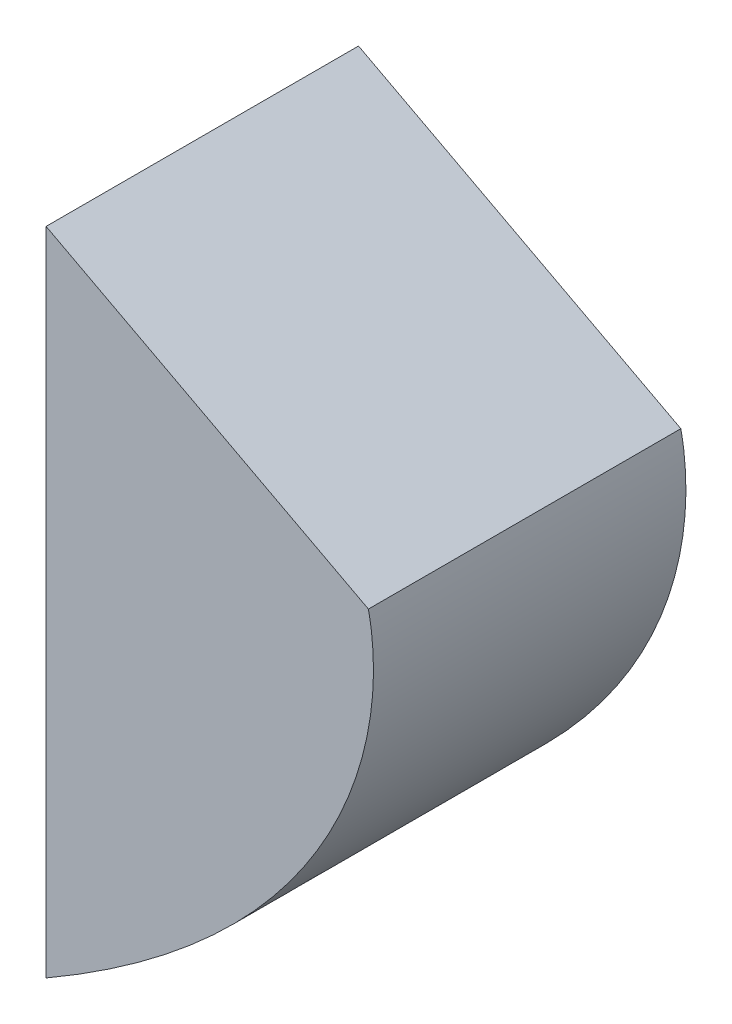
SolidWorks part; units mm, degrees
other "Gövde"
other "Kapak"
ref_plane "Ön Düzlem" through (0, 0, 0) normal (0, 0, 1) x (1, 0, 0)
ref_plane "Üst Düzlem" through (0, 0, 0) normal (0, 1, 0) x (1, 0, 0)
ref_plane "Sağ Düzlem" through (0, 0, 0) normal (1, 0, 0) x (0, 0, -1)
sketch "Çizim1" plane through (-22.056, 28.0016, 0) normal (0, 0, 1) x (1, 0, 0)
  line L0 (-37.0821, 414.1462) -> (-37.0821, -85.8538)
  spline S0 degree 1 poles (-37.0821, 414.1462) (210.4981, 283.3637) knots 0 0 1 1
  spline S1 degree 3 poles (210.4981, 283.3637) (227.475, 205.2647) (196.9692, 49.4286) (-37.0821, -85.8538) knots 0 0 0 0 1 1 1 1
  spline S2 degree 1 poles (15.7157, 483.7783) (256.3753, 340.6596) knots 0 0 1 1
  spline S3 degree 2 poles (15.7157, 483.7783) (225.5825, 567.9432) (256.3753, 340.6596) knots 0 0 0 1 1 1
  dimension "D2" = 280
  dimension "D1" = 500
extrude "Yükseklik-Ekstrüzyon2" add sketch "Çizim1" along normal blind 240
move or copy body "Gövde-Taşı/Kopyala1" bodies to move or copy 103 copy no translate (-44.4129, -54.698, 0)
move or copy body "Gövde-Taşı/Kopyala2" bodies to move or copy 104 copy no rotation origin (69.5765, 406.5638, 0) rotation axis (0, 0, 1) rotation angle 7
move or copy body "Gövde-Taşı/Kopyala3" bodies to move or copy 105 copy no rotation origin (72.1408, 412.9578, 0) rotation axis (0, 0, -1) rotation angle 4
move or copy body "Gövde-Taşı/Kopyala4" bodies to move or copy 106 copy no translate (0, -9.8176, 0)
move or copy body "Gövde-Taşı/Kopyala5" bodies to move or copy 107 copy no translate (-8.8826, 0, 0)
move or copy body "Gövde-Taşı/Kopyala6" bodies to move or copy 108 copy no translate (3.74, 1.87, 0)
delete or keep bodies "Gövde-Sil/Tut 1" type delete bodies bodies 109
hole_wizard "ust delik" positions "3B Çizim3" profile "Çizim4" hole size "M10x1.5" standard "ANSI Metrik"
sketch3d "3B Çizim3"
  line L0 (-59.1381, 442.1479, 240) -> (-59.1381, 442.1479, 0) construction
  line L1 (-59.1381, 442.1479, 240) -> (-59.1381, -57.8521, 240) construction
  point P0 (-59.1381, 362.1479, 120)
  point P2 (-59.1381, 362.1479, 120)
  dimension "D1" = 80
  dimension "D2" = 120
sketch "Çizim4" plane through (-59.1381, 362.1479, 120) normal (0, 1, 0) x (0, 0, 1)
  line L0 (0, 0) -> (0, 12.675)
  line L1 (0, 12.675) -> (5.25, 10)
  line L2 (5.25, 10) -> (5.25, 0)
  line L5 (5.25, 0) -> (0, 0)
  line L10 (0, 12.675) -> (-5.25, 10) construction
  line L11 (0, -6.35) -> (0, 107.95) construction
  dimension "Hole Dia." = 10.5
  dimension "Hole Depth" = 10
  dimension "Drill Angle" = 126
hole_wizard "alt delik" positions "3B Çizim4" profile "Çizim5" hole size "M10x1.5" standard "ANSI Metrik"
sketch3d "3B Çizim4"
  line L0 (-59.1381, 442.1479, 240) -> (-59.1381, -57.8521, 240) construction
  point P0 (-59.1381, 22.3842, 120)
  dimension "D1" = 340
  dimension "D2" = 120
sketch "Çizim5" plane through (-59.1381, 22.3842, 120) normal (0, 1, 0) x (0, 0, 1)
  line L0 (0, 0) -> (0, 13.1545)
  line L1 (0, 13.1545) -> (5.25, 10)
  line L2 (5.25, 10) -> (5.25, 0)
  line L5 (5.25, 0) -> (0, 0)
  line L10 (0, 13.1545) -> (-5.25, 10) construction
  line L11 (0, -6.35) -> (0, 107.95) construction
  dimension "Hole Dia." = 10.5
  dimension "Hole Depth" = 10
  dimension "Drill Angle" = 118
